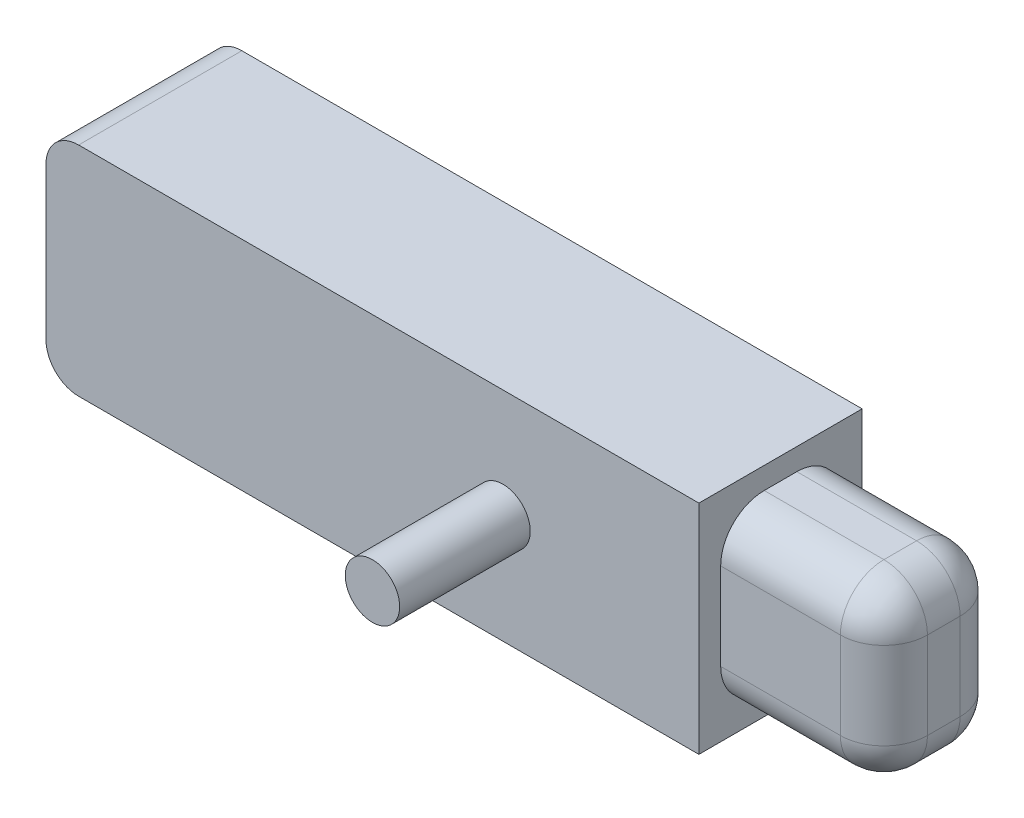
SolidWorks part; units mm, degrees
ref_plane "Front Plane" through (0, 0, 0) normal (0, 0, 1) x (1, 0, 0)
ref_plane "Top Plane" through (0, 0, 0) normal (0, 1, 0) x (1, 0, 0)
ref_plane "Right Plane" through (0, 0, 0) normal (1, 0, 0) x (0, 0, -1)
sketch "Sketch1" plane through (0, 0, 0) normal (0, 1, 0) x (1, 0, 0)
  line L1 (30, -7.5) -> (-30, -7.5)
  line L2 (30, -7.5) -> (30, 7.5)
  line L3 (30, 7.5) -> (-30, 7.5)
  line L4 (-30, -7.5) -> (-30, 7.5)
  line L5 (30, -7.5) -> (-30, 7.5) construction
  line L6 (30, 7.5) -> (-30, -7.5) construction
  point P0 (0, 0)
  dimension "D1" = 60
  dimension "D2" = 15
extrude "Boss-Extrude1" add sketch "Sketch1" along normal blind 20
sketch "Sketch2" plane through (0, 0, 7.5) normal (0, 0, 1) x (1, 0, 0)
  line L0 (-30, 20) -> (30, 20) construction
  line L1 (30, 20) -> (30, 0) construction
  circle A0 centre (12, 10) radius 2.5
  point P3 (0, 0)
  dimension "D1" = 5
  dimension "D2" = 18
  dimension "D3" = 10
extrude "Boss-Extrude2" add sketch "Sketch2" along normal blind 12
sketch "Sketch3" plane through (30, 0, 0) normal (1, 0, 0) x (0, 0, -1)
  line L0 (-7.5, 20) -> (7.5, 20) construction
  line L1 (5.5, 2) -> (-5.5, 2)
  line L2 (5.5, 2) -> (5.5, 18)
  line L3 (5.5, 18) -> (-5.5, 18)
  line L4 (-5.5, 2) -> (-5.5, 18)
  line L5 (5.5, 2) -> (-5.5, 18) construction
  line L6 (5.5, 18) -> (-5.5, 2) construction
  line L7 (-7.5, 0) -> (7.5, 0) construction
  line L9 (7.5, 20) -> (7.5, 0) construction
  line L10 (-7.5, 20) -> (-7.5, 0) construction
  point P0 (0, 10)
  dimension "D1" = 2
  dimension "D2" = 2
  dimension "D3" = 2
  dimension "D4" = 2
extrude "Boss-Extrude3" add sketch "Sketch3" along normal blind 15
fillet "Fillet1" radius 4 4 edges at (37.5, 18, 5.5) (37.5, 18, -5.5) (37.5, 2, -5.5) (37.5, 2, 5.5)
fillet "Fillet2" radius 4 8 edges at (45, 10, -5.5) (45, 3.1716, -4.3284) (45, 2, 0) (45, 3.1716, 4.3284) (45, 10, 5.5) (45, 16.8284, 4.3284) (45, 18, 0) (45, 16.8284, -4.3284)
fillet "Fillet3" radius 3 2 edges at (-30, 20, 0) (-30, 0, 0)
